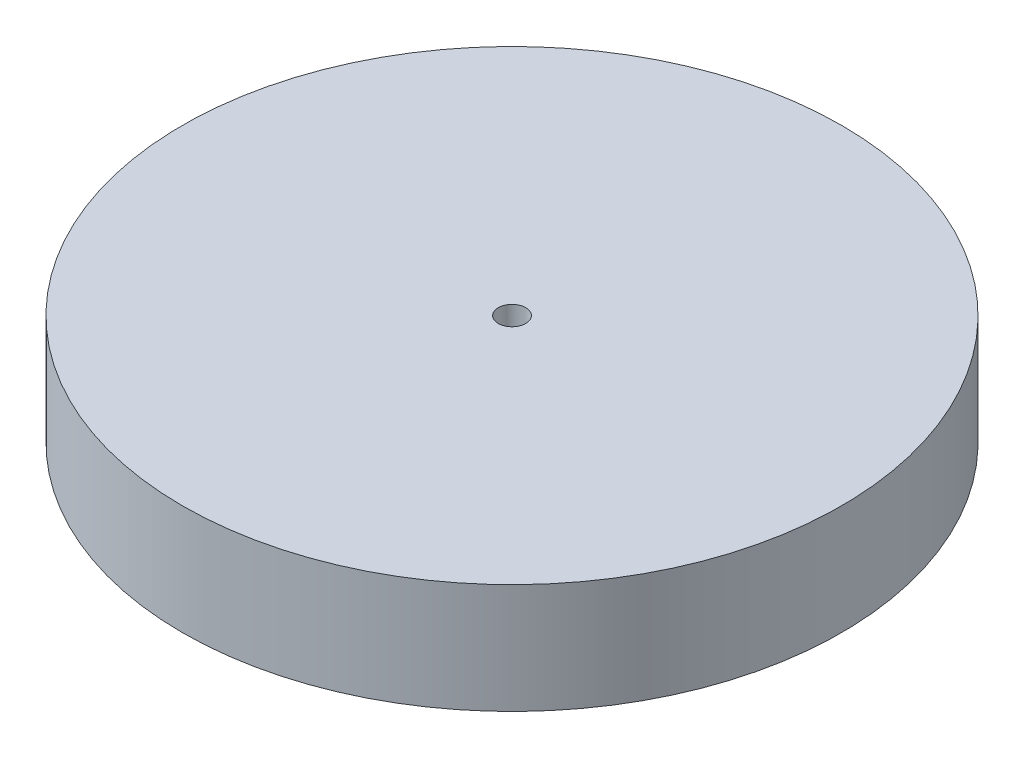
SolidWorks part; units mm, degrees
ref_plane "Front Plane" through (0, 0, 0) normal (0, 0, 1) x (1, 0, 0)
ref_plane "Top Plane" through (0, 0, 0) normal (0, 1, 0) x (1, 0, 0)
ref_plane "Right Plane" through (0, 0, 0) normal (1, 0, 0) x (0, 0, -1)
sketch "Sketch1" plane through (0, 0, 0) normal (0, 1, 0) x (1, 0, 0)
  circle A0 centre (0, 0) radius 152.4
  circle A1 centre (0, 0) radius 6.35
  dimension "D1" = 304.8
  dimension "D2" = 12.7
extrude "Boss-Extrude1" add sketch "Sketch1" along normal blind 50.8
